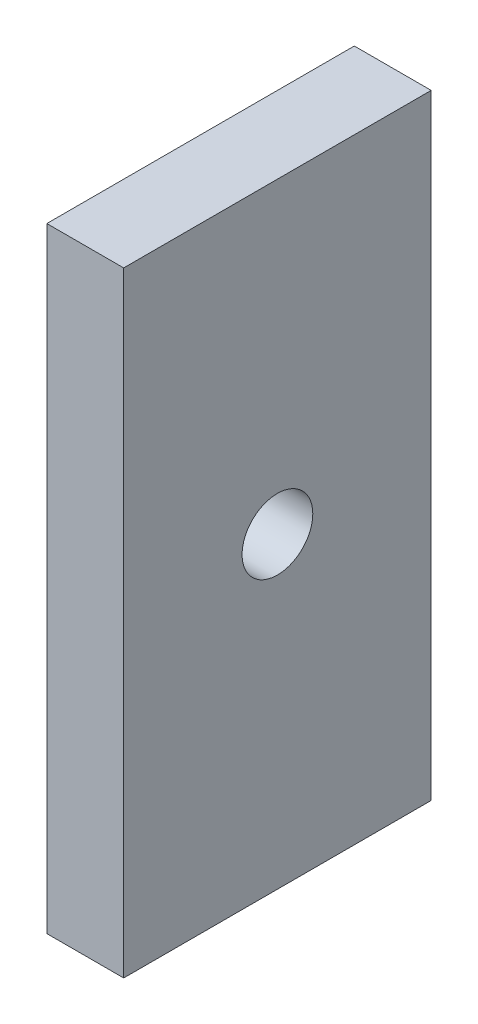
SolidWorks part; units mm, degrees
material "Acrylic (Medium-high impact)"
ref_plane "Front Plane" through (0, 0, 0) normal (0, 0, 1) x (1, 0, 0)
ref_plane "Top Plane" through (0, 0, 0) normal (0, 1, 0) x (1, 0, 0)
ref_plane "Right Plane" through (0, 0, 0) normal (1, 0, 0) x (0, 0, -1)
sketch "Sketch4" plane through (0, 0, 0) normal (1, 0, 0) x (0, 0, -1)
  line L1 (0, 0) -> (12.7, 0)
  line L2 (0, 0) -> (0, 25.4)
  line L3 (0, 25.4) -> (12.7, 25.4)
  line L4 (12.7, 0) -> (12.7, 25.4)
  dimension "D1" = 12.7
  dimension "D2" = 25.4
extrude "Boss-Extrude2" add sketch "Sketch4" along normal blind 3.175
sketch "Sketch5" plane through (3.175, 0, 0) normal (1, 0, 0) x (0, 0, -1)
  line L0 (0, 0) -> (12.7, 0) construction
  line L1 (0, 25.4) -> (0, 0) construction
  circle A0 centre (6.35, 12.7) radius 1.4605
  point P4 (6.35, 0)
  dimension "D1" = 2.921
  dimension "D2" = 12.7
  dimension "D3" = 6.35
extrude "Cut-Extrude1" cut sketch "Sketch5" against normal through all
